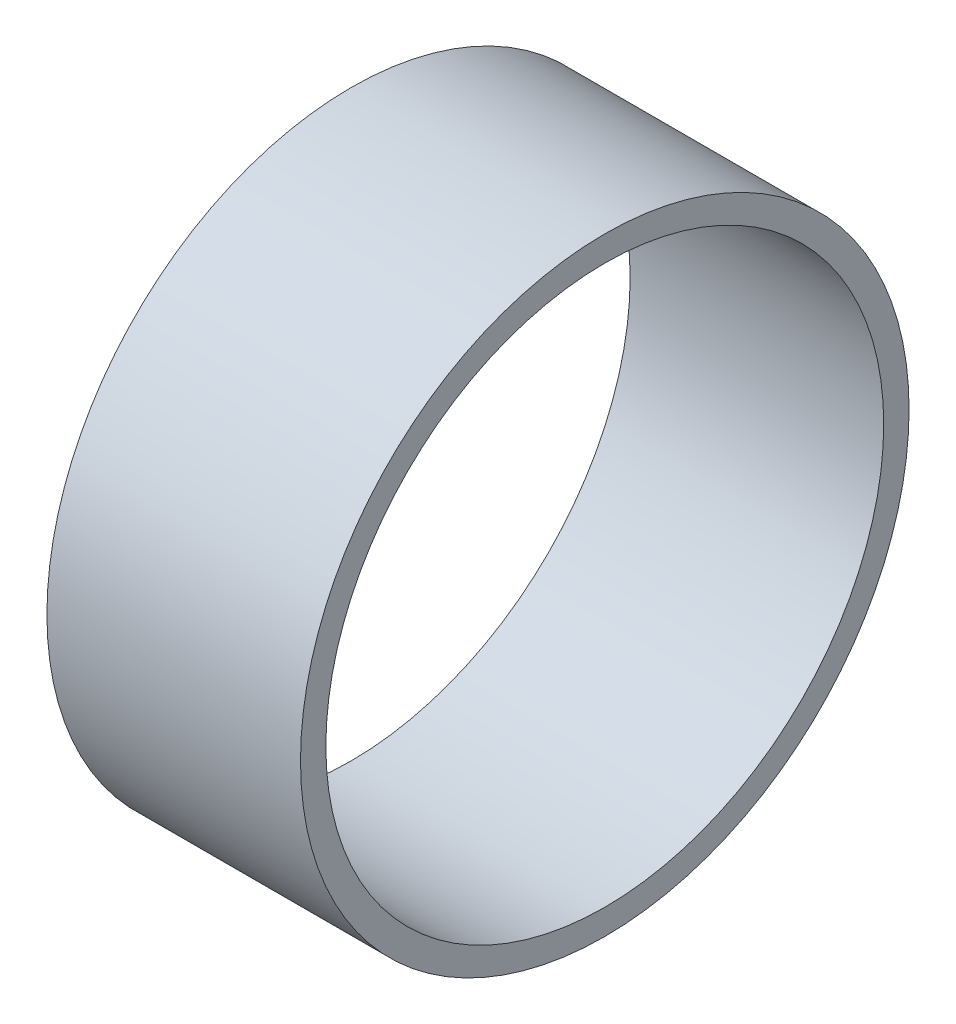
SolidWorks part; units mm, degrees
material "Rubber"
ref_plane "Front Plane" through (0, 0, 0) normal (0, 0, 1) x (1, 0, 0)
ref_plane "Top Plane" through (0, 0, 0) normal (0, 1, 0) x (1, 0, 0)
ref_plane "Right Plane" through (0, 0, 0) normal (1, 0, 0) x (0, 0, -1)
sketch "Sketch1" plane through (0, 0, 0) normal (0, 0, 1) x (1, 0, 0)
  line L1 (-63.5, 139.7) -> (63.5, 139.7)
  line L2 (-63.5, 139.7) -> (-63.5, 152.4)
  line L3 (-63.5, 152.4) -> (63.5, 152.4)
  line L4 (63.5, 139.7) -> (63.5, 152.4)
  line L5 (-63.5, 139.7) -> (63.5, 152.4) construction
  line L6 (-63.5, 152.4) -> (63.5, 139.7) construction
  point P0 (0, 146.05)
  dimension "D1" = 12.7
  dimension "D2" = 127
  dimension "D3" = 152.4
sketch "Sketch2" plane through (0, 0, 0) normal (0, 1, 0) x (1, 0, 0)
  line L0 (0, 0) -> (98.9029, 0) construction
revolve "Revolve1" add sketch "Sketch1" angle 360 about L0
equation "\"tire_thickness\"=0.5"
equation "\"D1@Sketch1\"=\"tire_thickness\""
equation "\"wheel_thickness\"=5"
equation "\"D2@Sketch1\"=\"wheel_thickness\""
equation "\"wheel_dia\"=12"
equation "\"D3@Sketch1\"=\"wheel_dia\"/2"
